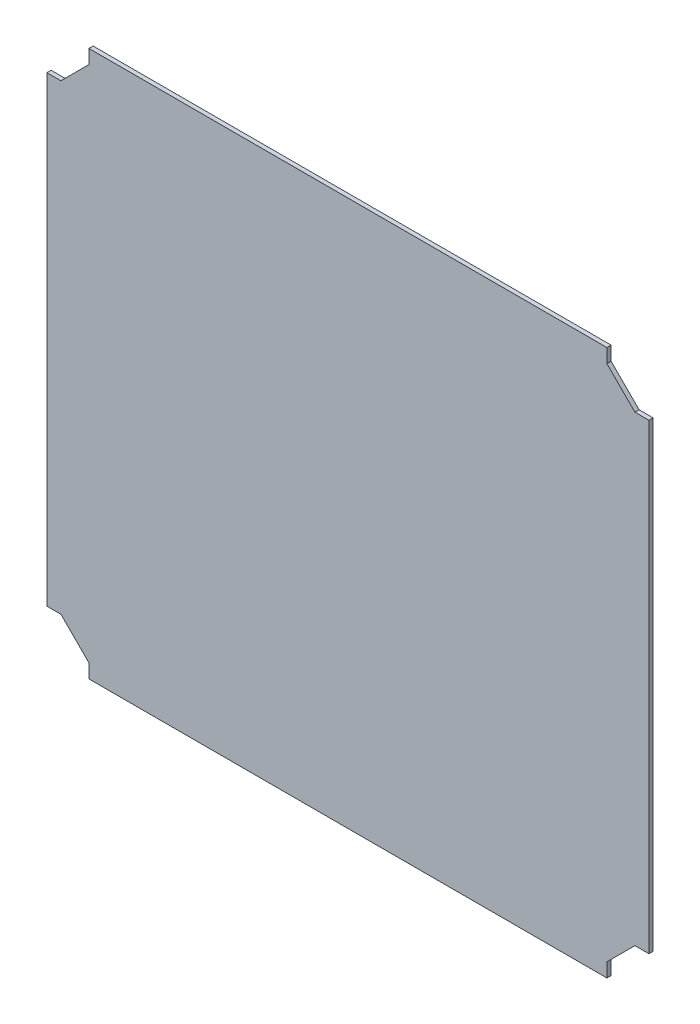
SolidWorks part; units mm, degrees
ref_plane "Alzado" through (0, 0, 0) normal (0, 0, 1) x (1, 0, 0)
ref_plane "Planta" through (0, 0, 0) normal (0, 1, 0) x (1, 0, 0)
ref_plane "Vista lateral" through (0, 0, 0) normal (1, 0, 0) x (0, 0, -1)
sketch "Sketch1" plane through (0, 0, 0) normal (0, 0, 1) x (1, 0, 0)
  line L1 (430, -390) -> (-430, -390)
  line L2 (430, -390) -> (430, 390)
  line L3 (430, 390) -> (-430, 390)
  line L4 (-430, -390) -> (-430, 390)
  line L5 (430, -390) -> (-430, 390) construction
  line L6 (430, 390) -> (-430, -390) construction
  point P0 (0, 0)
  dimension "D1" = 860
  dimension "D2" = 780
extrude "Boss-Extrude1" add sketch "Sketch1" along normal blind 6
sketch "Sketch2" plane through (0, 0, 6) normal (0, 0, 1) x (1, 0, 0)
  line L1 (-430, 390) -> (-370, 390)
  line L2 (-430, 390) -> (-430, 330)
  line L3 (-430, 330) -> (-370, 330)
  line L4 (-370, 390) -> (-370, 330)
  line L5 (430, 390) -> (370, 390)
  line L6 (430, 390) -> (430, 330)
  line L7 (430, 330) -> (370, 330)
  line L8 (370, 390) -> (370, 330)
  line L9 (430, -390) -> (370, -390)
  line L10 (430, -390) -> (430, -330)
  line L11 (430, -330) -> (370, -330)
  line L12 (370, -390) -> (370, -330)
  line L13 (-430, -390) -> (-370, -390)
  line L14 (-430, -390) -> (-430, -330)
  line L15 (-430, -330) -> (-370, -330)
  line L16 (-370, -390) -> (-370, -330)
  point P20 (315.3405, -275.3405)
  dimension "D1" = 60
extrude "Cut-Extrude1" cut sketch "Sketch2" against normal up to surface (6 mm away) up to face at (0, 0, 0)
chamfer "Chamfer1" distance 40 angle 45 4 edges at (-370, -330, 3) (370, -330, 3) (370, 330, 3) (-370, 330, 3)
